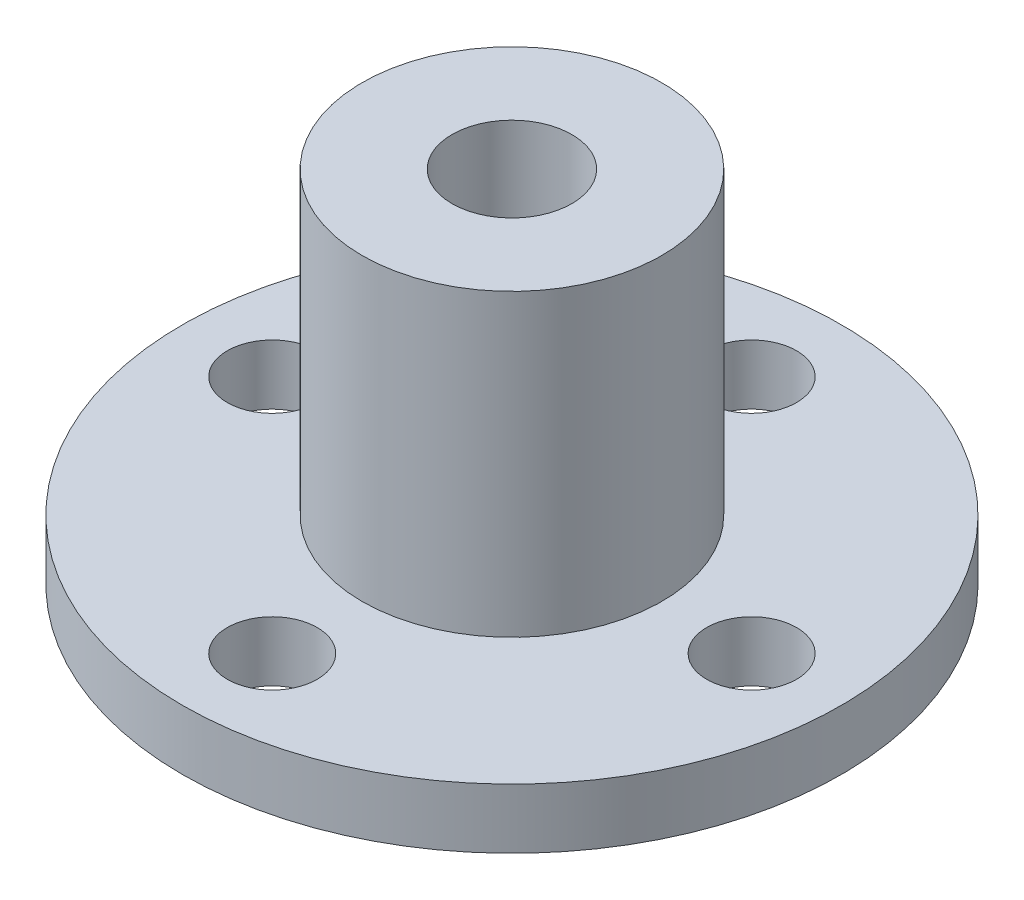
SolidWorks part; units mm, degrees
material "6061 Alloy"
ref_plane "Front Plane" through (0, 0, 0) normal (0, 0, 1) x (1, 0, 0)
ref_plane "Top Plane" through (0, 0, 0) normal (0, 1, 0) x (1, 0, 0)
ref_plane "Right Plane" through (0, 0, 0) normal (1, 0, 0) x (0, 0, -1)
sketch "Sketch1" plane through (0, 0, 0) normal (0, 1, 0) x (1, 0, 0)
  circle A0 centre (0, 0) radius 11
  dimension "D1" = 22
extrude "Boss-Extrude1" add sketch "Sketch1" along normal blind 2
sketch "Sketch2" plane through (0, 2, 0) normal (0, 1, 0) x (1, 0, 0)
  circle A0 centre (0, 0) radius 5
  dimension "D1" = 10
extrude "Boss-Extrude2" add sketch "Sketch2" along normal blind 10
sketch "Sketch3" plane through (0, 12, 0) normal (0, 1, 0) x (1, 0, 0)
  circle A0 centre (0, 0) radius 2
  dimension "D1" = 4
extrude "Cut-Extrude1" cut sketch "Sketch3" against normal through all
sketch "Sketch4" plane through (0, 2, 0) normal (0, 1, 0) x (1, 0, 0)
  circle A0 centre (-8, 0) radius 1.5
  dimension "D2" = 3
  dimension "D1" = 8
extrude "Cut-Extrude2" cut sketch "Sketch4" against normal through all
pattern_circular "CirPattern1" count 4 over 360 about axis through (0, 0, 0) along (0, 1, 0) of "Cut-Extrude2"
